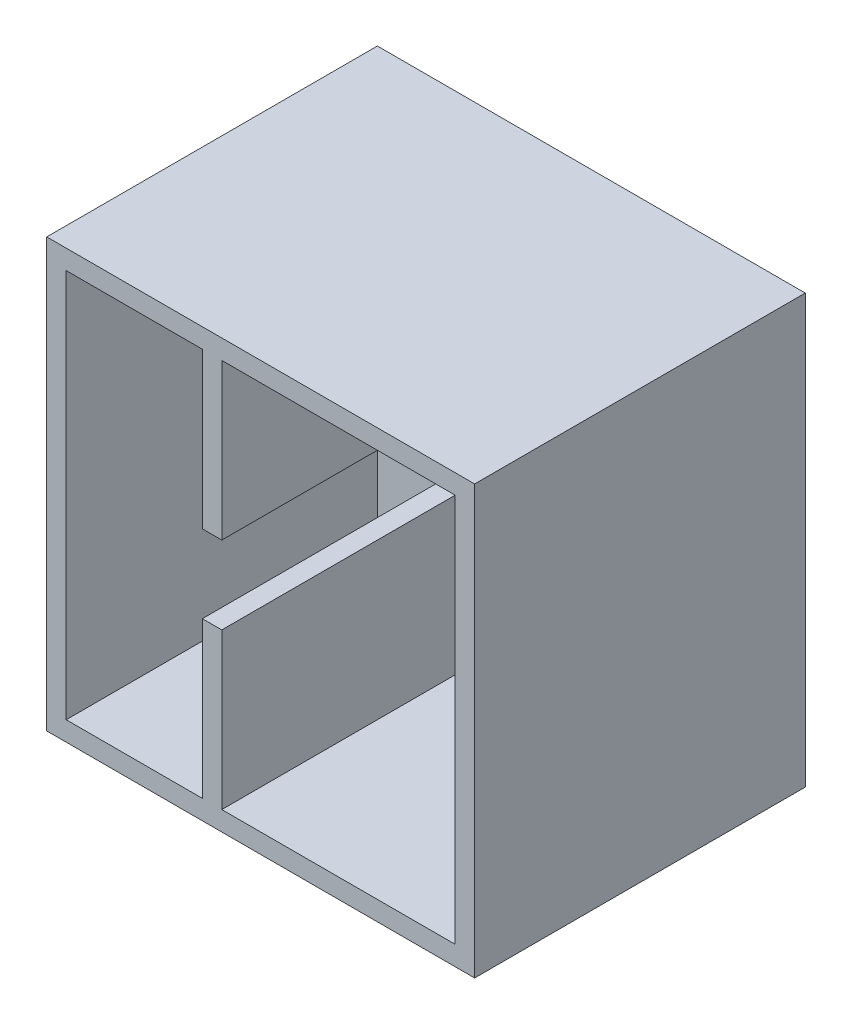
SolidWorks part; units mm, degrees
ref_plane "Front Plane" through (0, 0, 0) normal (0, 0, 1) x (1, 0, 0)
ref_plane "Top Plane" through (0, 0, 0) normal (0, 1, 0) x (1, 0, 0)
ref_plane "Right Plane" through (0, 0, 0) normal (1, 0, 0) x (0, 0, -1)
sketch "Sketch1" plane through (0, 0, 0) normal (0, 0, 1) x (1, 0, 0)
  line L0 (1100, 1100) -> (-1100, 1100)
  line L1 (1000, -1000) -> (-200, -1000)
  line L2 (1000, -1000) -> (1000, 1000)
  line L3 (1000, 1000) -> (-200, 1000)
  line L4 (-1000, -1000) -> (-1000, 1000)
  line L5 (1000, -1000) -> (-1000, 1000) construction
  line L6 (1000, 1000) -> (-1000, -1000) construction
  line L7 (-1100, -1100) -> (-1100, 1100)
  line L8 (1100, -1100) -> (-1100, -1100)
  line L9 (1100, -1100) -> (1100, 1100)
  line L10 (-300, -1000) -> (-300, -200)
  line L11 (-300, -200) -> (-200, -200)
  line L12 (-200, -200) -> (-200, -1000)
  line L13 (-300, 1000) -> (-300, 200)
  line L14 (-300, 200) -> (-200, 200)
  line L15 (-200, 200) -> (-200, 1000)
  line L16 (-1000, 0) -> (1000, 0) construction
  line L17 (-300, 1000) -> (-1000, 1000)
  line L18 (1000, 1000) -> (-1000, 1000) construction
  line L19 (-300, -1000) -> (-1000, -1000)
  line L20 (1000, -1000) -> (-1000, -1000) construction
  point P0 (0, 0)
  point P20 (-250, -200)
  dimension "D1" = 2000
  dimension "D2" = 2000
  dimension "D4" = 700
  dimension "D5" = 100
  dimension "D6" = 200
  dimension "D7" = 200
  dimension "D3" = 100
extrude "Boss-Extrude1" add sketch "Sketch1" along normal blind 1700
sketch "Sketch2" plane through (0, 0, 0) normal (0, 0, -1) x (-1, 0, 0)
  line L1 (1100, -1100) -> (-1100, -1100)
  line L2 (1100, -1100) -> (1100, 1100)
  line L3 (1100, 1100) -> (-1100, 1100)
  line L4 (-1100, -1100) -> (-1100, 1100)
extrude "Boss-Extrude2" add sketch "Sketch2" against normal blind 100
